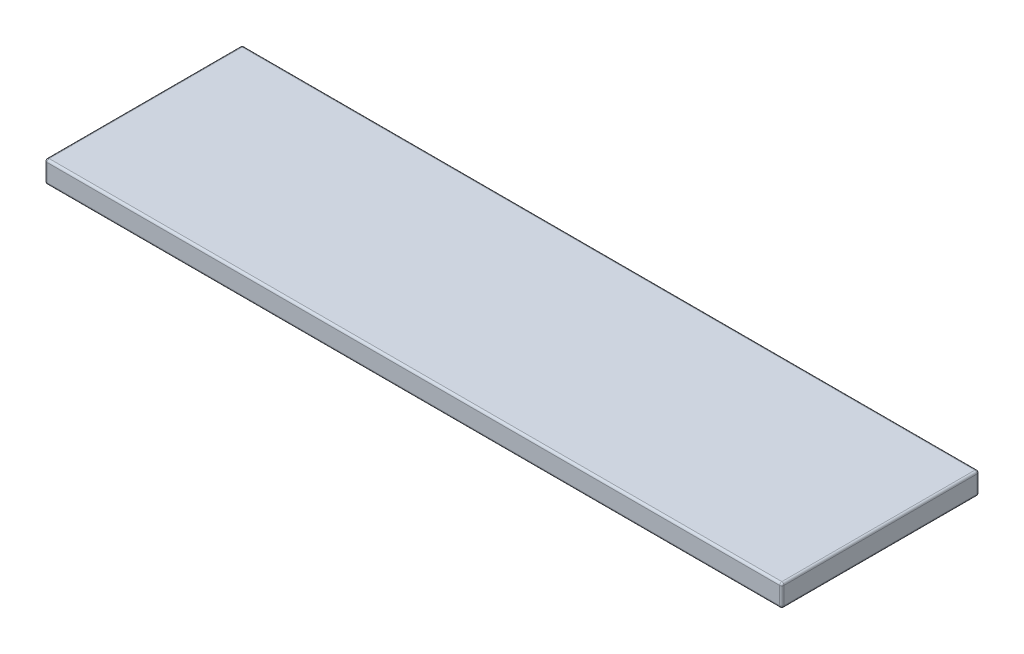
SolidWorks part; units mm, degrees
material "Balsa"
ref_plane "Plano frontal" through (0, 0, 0) normal (0, 0, 1) x (1, 0, 0)
ref_plane "Plano superior" through (0, 0, 0) normal (0, 1, 0) x (1, 0, 0)
ref_plane "Plano direito" through (0, 0, 0) normal (1, 0, 0) x (0, 0, -1)
sketch "Esboço1" plane through (0, 0, 0) normal (0, 1, 0) x (1, 0, 0)
  line L1 (-84, -22.5) -> (84, -22.5)
  line L2 (-84, -22.5) -> (-84, 22.5)
  line L3 (-84, 22.5) -> (84, 22.5)
  line L4 (84, -22.5) -> (84, 22.5)
  line L5 (-84, -22.5) -> (84, 22.5) construction
  line L6 (-84, 22.5) -> (84, -22.5) construction
  point P0 (0, 0)
  dimension "D1" = 168
  dimension "D2" = 45
extrude "Ressalto-extrusão1" add sketch "Esboço1" along normal blind 5
fillet "Filete1" radius 0.5 12 edges at (84, 2.5, -22.5) (-84, 2.5, -22.5) (-84, 2.5, 22.5) (84, 2.5, 22.5) (0, 5, 22.5) (-84, 5, 0) (0, 5, -22.5) (84, 5, 0) (0, 0, -22.5) (-84, 0, 0) (0, 0, 22.5) (84, 0, 0)
